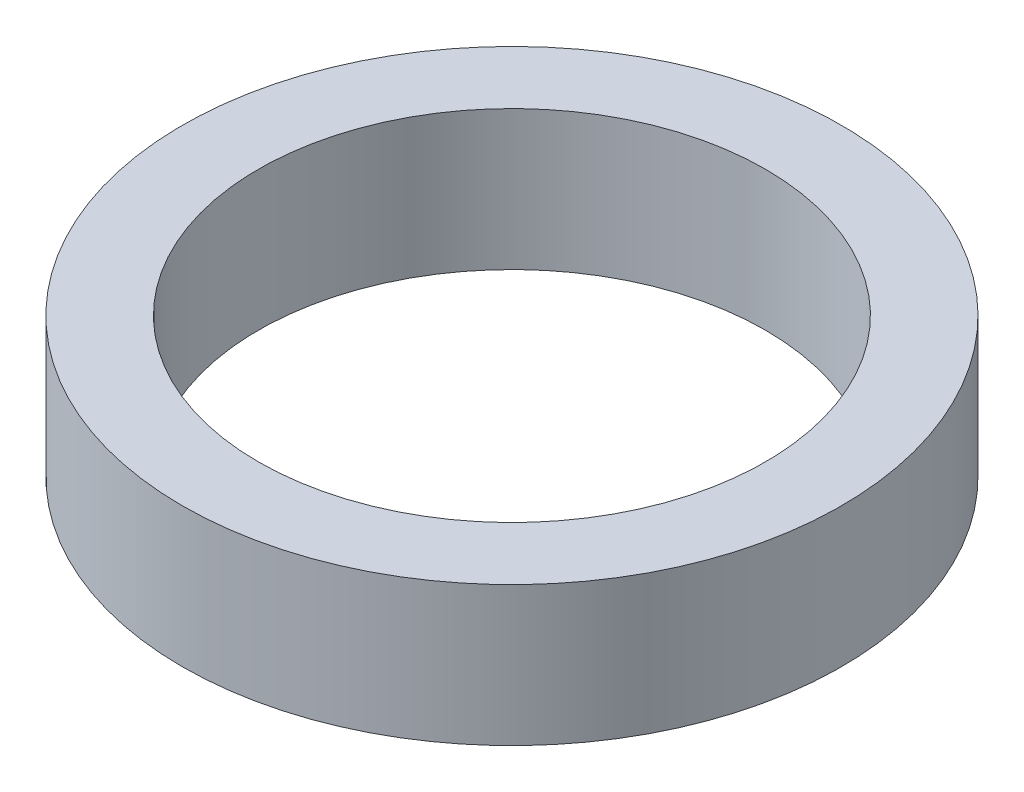
SolidWorks part; units mm, degrees
material "1.4511 (X3CrNb17)"
ref_plane "前视基准面" through (0, 0, 0) normal (0, 0, 1) x (1, 0, 0)
ref_plane "上视基准面" through (0, 0, 0) normal (0, 1, 0) x (1, 0, 0)
ref_plane "右视基准面" through (0, 0, 0) normal (1, 0, 0) x (0, 0, -1)
sketch "草图1" plane through (0, 0, 0) normal (0, 1, 0) x (1, 0, 0)
  circle A0 centre (0, 0) radius 13
  dimension "D1" = 26
extrude "凸台-拉伸1" add sketch "草图1" along normal blind 5.5
sketch "草图2" plane through (0, 5.5, 0) normal (0, 1, 0) x (1, 0, 0)
  circle A0 centre (0, 0) radius 10
  dimension "D1" = 20
extrude "切除-拉伸1" cut sketch "草图2" against normal blind 5.5
